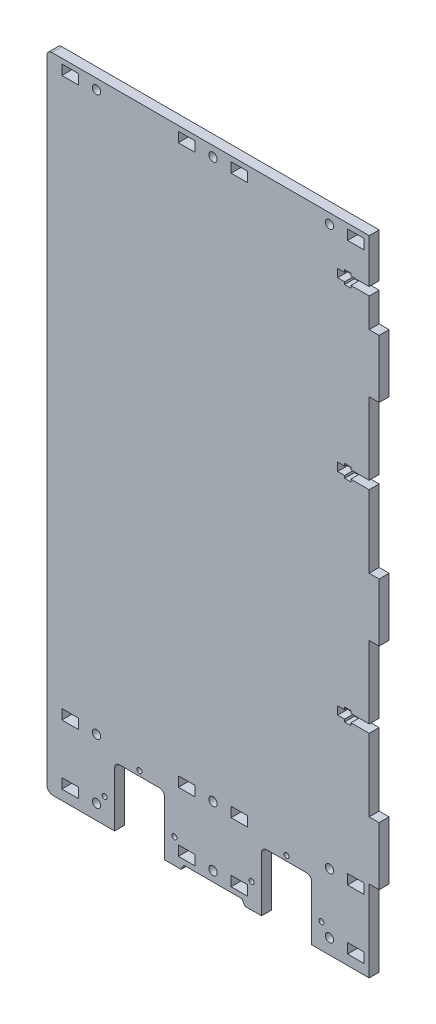
SolidWorks part; units mm, degrees
ref_plane "Спереди" through (0, 0, 0) normal (0, 0, 1) x (1, 0, 0)
ref_plane "Сверху" through (0, 0, 0) normal (0, 1, 0) x (1, 0, 0)
ref_plane "Справа" through (0, 0, 0) normal (1, 0, 0) x (0, 0, -1)
sketch "Эскиз1" plane through (0, 0, 0) normal (0, 0, 1) x (1, 0, 0)
  line L0 (81, 0) -> (91, 0) construction
  line L1 (91, 0) -> (91, 6) construction
  line L2 (91, 6) -> (81, 6) construction
  line L3 (81, 6) -> (81, 0) construction
  line L4 (10.8625, 0) -> (20.8625, 0) construction
  line L5 (20.8625, 0) -> (20.8625, 6) construction
  line L6 (20.8625, 6) -> (10.8625, 6) construction
  line L7 (10.8625, 6) -> (10.8625, 0) construction
  line L8 (-20.8625, 0) -> (-10.8625, 0) construction
  line L9 (-10.8625, 0) -> (-10.8625, 6) construction
  line L10 (-10.8625, 6) -> (-20.8625, 6) construction
  line L11 (-20.8625, 6) -> (-20.8625, 0) construction
  line L12 (-91, 0) -> (-81, 0) construction
  line L13 (-81, 0) -> (-81, 6) construction
  line L14 (-81, 6) -> (-91, 6) construction
  line L15 (-91, 6) -> (-91, 0) construction
  line L16 (81, 0) -> (91, 0)
  line L17 (91, 0) -> (91, 6)
  line L18 (91, 6) -> (81, 6)
  line L19 (81, 6) -> (81, 0)
  line L20 (10.8625, 0) -> (20.8625, 0)
  line L21 (20.8625, 0) -> (20.8625, 6)
  line L22 (20.8625, 6) -> (10.8625, 6)
  line L23 (10.8625, 6) -> (10.8625, 0)
  line L24 (-20.8625, 0) -> (-10.8625, 0)
  line L25 (-10.8625, 0) -> (-10.8625, 6)
  line L26 (-10.8625, 6) -> (-20.8625, 6)
  line L27 (-20.8625, 6) -> (-20.8625, 0)
  line L28 (-91, 0) -> (-81, 0)
  line L29 (-81, 0) -> (-81, 6)
  line L30 (-81, 6) -> (-91, 6)
  line L31 (-91, 6) -> (-91, 0)
  line L32 (-72.5875, 3) -> (-67.6875, 3) construction
  line L33 (-72.5875, 6) -> (-72.5875, 0) construction
  line L34 (-67.6875, 6) -> (-67.6875, 0) construction
  line L35 (-2.45, 3) -> (2.45, 3) construction
  line L36 (-2.45, 6) -> (-2.45, 0) construction
  line L37 (2.45, 6) -> (2.45, 0) construction
  line L38 (0, 0) -> (0, 50000) construction
  line L39 (81, -336) -> (91, -336)
  line L40 (91, -336) -> (91, -330)
  line L41 (91, -330) -> (81, -330)
  line L42 (81, -330) -> (81, -336)
  line L43 (10.8625, -336) -> (20.8625, -336)
  line L44 (20.8625, -336) -> (20.8625, -330)
  line L45 (20.8625, -330) -> (10.8625, -330)
  line L46 (10.8625, -330) -> (10.8625, -336)
  line L47 (-20.8625, -336) -> (-10.8625, -336)
  line L48 (-10.8625, -336) -> (-10.8625, -330)
  line L49 (-10.8625, -330) -> (-20.8625, -330)
  line L50 (-20.8625, -330) -> (-20.8625, -336)
  line L51 (-91, -336) -> (-81, -336)
  line L52 (-81, -336) -> (-81, -330)
  line L53 (-81, -330) -> (-91, -330)
  line L54 (-91, -330) -> (-91, -336)
  line L55 (81, -372) -> (91, -372)
  line L56 (91, -372) -> (91, -366)
  line L57 (91, -366) -> (81, -366)
  line L58 (81, -366) -> (81, -372)
  line L59 (10.8625, -372) -> (20.8625, -372)
  line L60 (20.8625, -372) -> (20.8625, -366)
  line L61 (20.8625, -366) -> (10.8625, -366)
  line L62 (10.8625, -366) -> (10.8625, -372)
  line L63 (-20.8625, -372) -> (-10.8625, -372)
  line L64 (-10.8625, -372) -> (-10.8625, -366)
  line L65 (-10.8625, -366) -> (-20.8625, -366)
  line L66 (-20.8625, -366) -> (-20.8625, -372)
  line L67 (-91, -372) -> (-81, -372)
  line L68 (-81, -372) -> (-81, -366)
  line L69 (-81, -366) -> (-91, -366)
  line L70 (-91, -366) -> (-91, -372)
  line L72 (-100, 9) -> (-100, -378)
  line L73 (-100, -378) -> (-19.2321, -378) construction
  line L74 (-19.2321, -378) -> (-17.5, -375)
  line L75 (-17.5, -375) -> (17.5, -375)
  line L76 (19.2321, -378) -> (17.5, -375)
  line L78 (-100, 0) -> (-100, 6) construction
  line L79 (100, 8.9546) -> (100, -378.0227) construction
  line L80 (-100, 9) -> (94, 9)
  line L81 (94, 9) -> (94, -40) construction
  line L82 (94, -40) -> (100, -40)
  line L83 (94, 6) -> (94, 0) construction
  line L84 (100, -40) -> (100, -75)
  line L85 (100, -75) -> (94, -75)
  line L87 (-100, -378) -> (-59.25, -378)
  line L88 (94, -329) -> (100, -329)
  line L89 (100, 6) -> (100, 0) construction
  line L90 (100, -329) -> (100, -294)
  line L91 (100, -294) -> (94, -294)
  line L93 (267.8513, -184.5) -> (-49732.1487, -184.5) construction
  line L94 (94, -75) -> (94, -167) construction
  line L95 (94, -167) -> (100, -167)
  line L96 (100, -167) -> (100, -202)
  line L97 (100, -202) -> (94, -202)
  line L98 (94, 9) -> (94, -17.55)
  line L99 (94, -17.55) -> (83, -17.55)
  line L100 (83, -17.55) -> (83, -16.075)
  line L101 (83, -16.075) -> (79.2, -16.075)
  line L102 (79.2, -16.075) -> (79.2, -17.55)
  line L103 (79.2, -17.55) -> (75, -17.55)
  line L104 (75, -17.55) -> (75, -22.45)
  line L105 (68.6956, -20) -> (105.6963, -20) construction
  line L106 (79.2, -22.45) -> (75, -22.45)
  line L107 (79.2, -23.925) -> (79.2, -22.45)
  line L108 (83, -23.925) -> (79.2, -23.925)
  line L109 (83, -22.45) -> (83, -23.925)
  line L110 (94, -22.45) -> (83, -22.45)
  line L111 (94, -22.45) -> (94, -40)
  line L112 (81, -40) -> (91, -40) construction
  line L113 (94, -118.55) -> (83, -118.55)
  line L114 (83, -118.55) -> (83, -117.075)
  line L115 (83, -117.075) -> (79.2, -117.075)
  line L116 (79.2, -117.075) -> (79.2, -118.55)
  line L117 (79.2, -118.55) -> (75, -118.55)
  line L118 (75, -118.55) -> (75, -123.45)
  line L119 (79.2, -123.45) -> (75, -123.45)
  line L120 (79.2, -124.925) -> (79.2, -123.45)
  line L121 (83, -124.925) -> (79.2, -124.925)
  line L122 (83, -123.45) -> (83, -124.925)
  line L123 (94, -123.45) -> (83, -123.45)
  line L124 (48.0583, -121) -> (131.1899, -121) construction
  line L125 (94, -75) -> (94, -118.55)
  line L126 (94, -123.45) -> (94, -167)
  line L127 (94, -245.55) -> (83, -245.55)
  line L128 (83, -245.55) -> (83, -244.075)
  line L129 (83, -244.075) -> (79.2, -244.075)
  line L130 (79.2, -244.075) -> (79.2, -245.55)
  line L131 (79.2, -245.55) -> (75, -245.55)
  line L132 (75, -250.45) -> (75, -245.55)
  line L133 (79.2, -250.45) -> (75, -250.45)
  line L134 (79.2, -251.925) -> (79.2, -250.45)
  line L135 (83, -251.925) -> (79.2, -251.925)
  line L136 (83, -250.45) -> (83, -251.925)
  line L137 (94, -250.45) -> (83, -250.45)
  line L151 (94, -294) -> (94, -250.45)
  line L152 (94, -245.55) -> (94, -202)
  line L153 (-59.25, -378) -> (-59.25, -342)
  line L154 (-59.25, -342) -> (-29.25, -342)
  line L155 (-29.25, -342) -> (-29.25, -378)
  line L156 (-29.25, -378) -> (-19.2321, -378)
  line L157 (-67.6875, -336) -> (-20.8625, -336) construction
  line L158 (-44.25, -321.7106) -> (-44.25, -398.7375) construction
  line L159 (-67.6375, -369) -> (-59.25, -369) construction
  line L160 (-20.8625, -369) -> (-29.25, -369) construction
  line L161 (29.25, -378) -> (19.2321, -378)
  line L162 (29.25, -342) -> (29.25, -378)
  line L163 (59.25, -342) -> (29.25, -342)
  line L164 (59.25, -378) -> (59.25, -342)
  line L165 (59.25, -378) -> (94, -378)
  line L166 (94, -378) -> (94, -329)
  circle A0 centre (-70.1375, 3) radius 2.5
  circle A1 centre (0, 3) radius 2.5
  circle A2 centre (70.1375, 3) radius 2.5
  circle A3 centre (-70.1375, -333) radius 2.5
  circle A4 centre (0, -333) radius 2.5
  circle A5 centre (70.1375, -333) radius 2.5
  circle A6 centre (-70.1375, -369) radius 2.5
  circle A7 centre (0, -369) radius 2.5
  circle A8 centre (70.1375, -369) radius 2.5
  circle A9 centre (-65.25, -363) radius 1.5
  circle A10 centre (-44.25, -339) radius 1.5
  circle A11 centre (-23.25, -363) radius 1.5
  circle A12 centre (23.25, -363) radius 1.5
  circle A13 centre (44.25, -339) radius 1.5
  circle A14 centre (65.25, -363) radius 1.5
  point P112 (100, -184.5)
  point P123 (75, -20)
  point P131 (-100, -184.5)
  point P146 (94, -121)
  point P147 (75, -121)
  point P178 (-44.25, -342)
  dimension "D1" = 5
  dimension "D23" = 3
  dimension "D4" = 330
  dimension "D5" = 30
  dimension "D7" = 35
  dimension "D6" = 60
  dimension "D8" = 3
  dimension "D9" = 3
  dimension "D10" = 3
  dimension "D11" = 35
  dimension "D12" = 25
  dimension "D13" = 3.8
  dimension "D14" = 17
  dimension "D15" = 4.9
  dimension "D16" = 7.85
  dimension "D17" = 20
  dimension "D19" = 30
  dimension "D20" = 6
  dimension "D21" = 3
  dimension "D22" = 3
  dimension "D24" = 42
  dimension "D2" = 2
  dimension "D3" = 2
  dimension "D18" = 2
extrude "Бобышка-Вытянуть1" add sketch "Эскиз1" along normal blind 6
fillet "Скругление1" radius 3 5 edges at (-100, 9, 3) (-59.25, -342, 3) (29.25, -342, 3) (59.25, -342, 3) (-29.25, -342, 3)
fillet "Скругление2" radius 3.5 1 edges at (-100, -378, 3)
equation "\"D4@Эскиз1\"=300+30"
